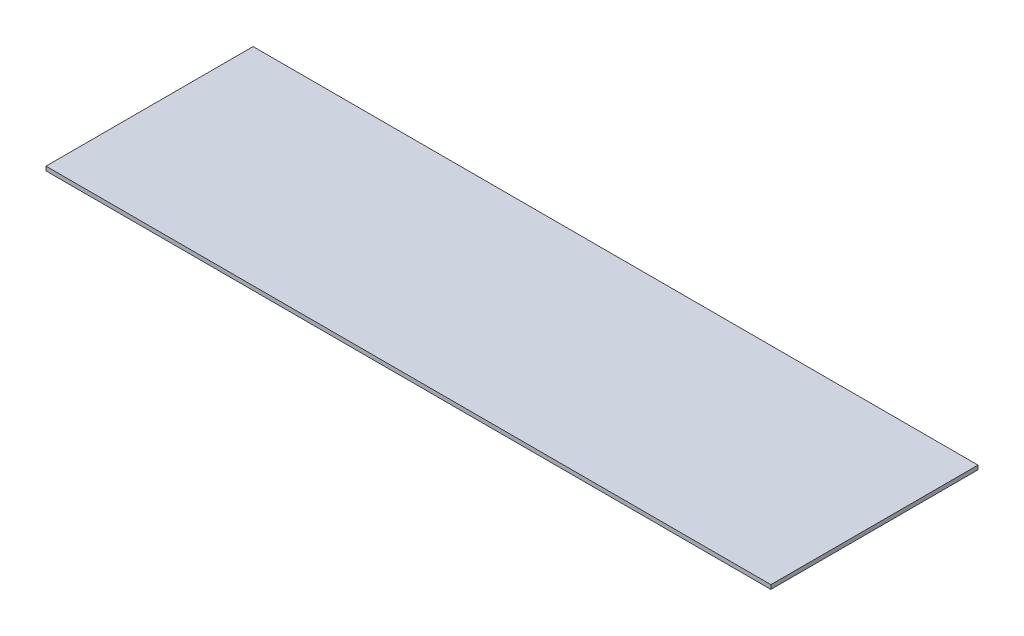
SolidWorks part; units mm, degrees
ref_plane "Front Plane" through (0, 0, 0) normal (0, 0, 1) x (1, 0, 0)
ref_plane "Top Plane" through (0, 0, 0) normal (0, 1, 0) x (1, 0, 0)
ref_plane "Right Plane" through (0, 0, 0) normal (1, 0, 0) x (0, 0, -1)
sketch "Sketch1" plane through (0, 0, 0) normal (0, 1, 0) x (1, 0, 0)
  line L1 (0, 0) -> (350, 0)
  line L2 (0, 0) -> (0, -100)
  line L3 (0, -100) -> (350, -100)
  line L4 (350, 0) -> (350, -100)
  dimension "D1" = 350
  dimension "D2" = 100
extrude "Boss-Extrude1" add sketch "Sketch1" along normal blind 2
